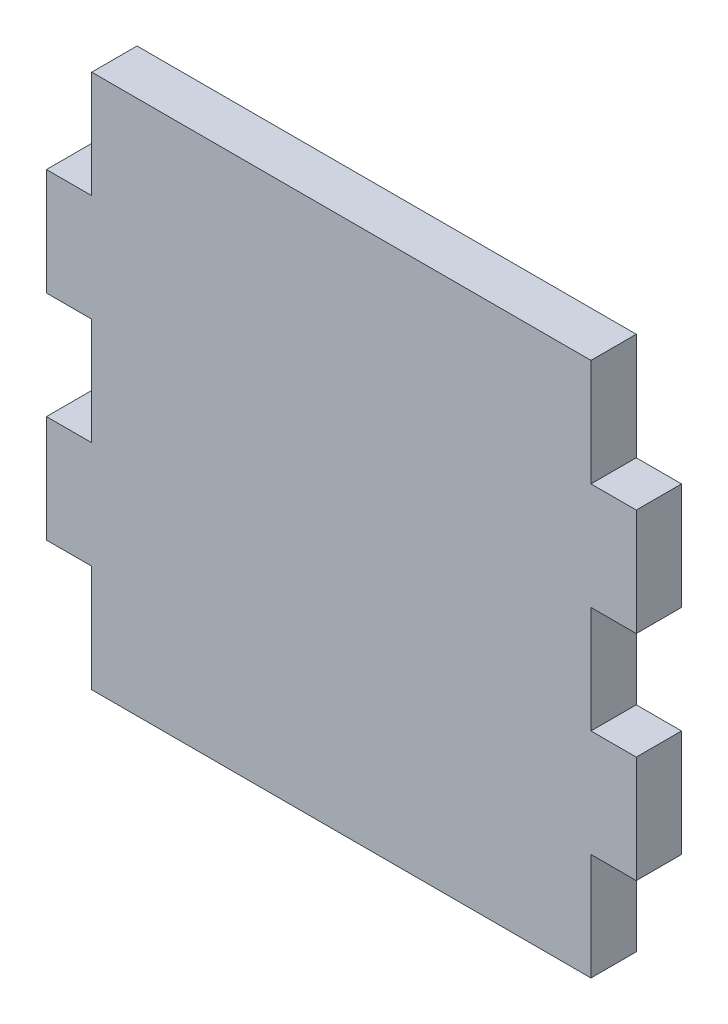
SolidWorks part; units mm, degrees
ref_plane "Front Plane" through (0, 0, 0) normal (0, 0, 1) x (1, 0, 0)
ref_plane "Top Plane" through (0, 0, 0) normal (0, 1, 0) x (1, 0, 0)
ref_plane "Right Plane" through (0, 0, 0) normal (1, 0, 0) x (0, 0, -1)
sketch "Sketch1" plane through (0, 0, 0) normal (0, 0, 1) x (1, 0, 0)
  line L0 (-70, 75) -> (-70, 60)
  line L1 (0, 0) -> (-70, 0)
  line L2 (0, 75) -> (0, 60)
  line L3 (0, 75) -> (-70, 75)
  line L4 (0, 15) -> (0, 0)
  line L5 (-70, 60) -> (-76.35, 60)
  line L6 (-76.35, 60) -> (-76.35, 45)
  line L7 (-76.35, 45) -> (-70, 45)
  line L8 (-70, 45) -> (-70, 30)
  line L9 (-70, 30) -> (-76.35, 30)
  line L10 (-76.35, 30) -> (-76.35, 15)
  line L11 (-76.35, 15) -> (-70, 15)
  line L12 (-70, 15) -> (-70, 0)
  line L13 (-35, 75) -> (-35, 0) construction
  line L14 (-70, 60) -> (-70, 45) construction
  line L15 (-70, 30) -> (-70, 15) construction
  line L16 (0, 30) -> (0, 15) construction
  line L17 (0, 60) -> (0, 45) construction
  line L18 (6.35, 15) -> (0, 15)
  line L19 (6.35, 30) -> (6.35, 15)
  line L20 (0, 30) -> (6.35, 30)
  line L21 (0, 45) -> (0, 30)
  line L22 (6.35, 45) -> (0, 45)
  line L23 (6.35, 60) -> (6.35, 45)
  line L24 (0, 60) -> (6.35, 60)
  dimension "D1" = 35
  dimension "D2" = 75
  dimension "D3" = 6.35
extrude "Body" add sketch "Sketch1" along normal blind 6.35
